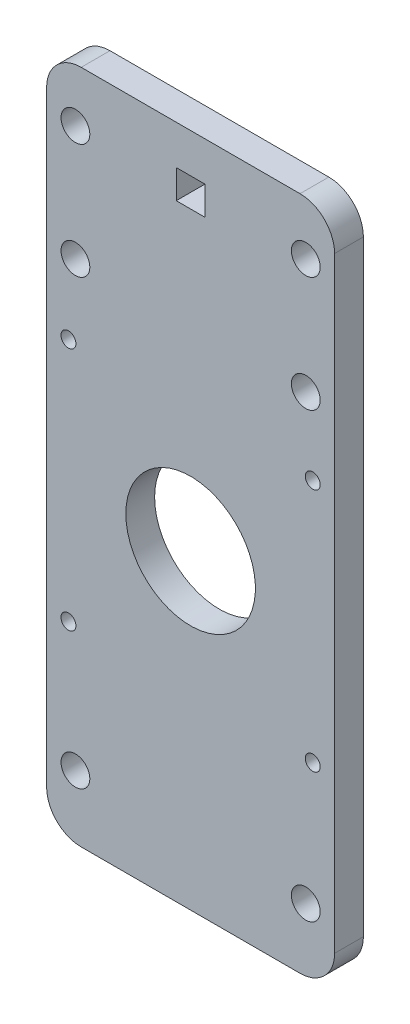
SolidWorks part; units mm, degrees
ref_plane "Front Plane" through (0, 0, 0) normal (0, 0, 1) x (1, 0, 0)
ref_plane "Top Plane" through (0, 0, 0) normal (0, 1, 0) x (1, 0, 0)
ref_plane "Right Plane" through (0, 0, 0) normal (1, 0, 0) x (0, 0, -1)
sketch "Sketch1" plane through (0, 0, 0) normal (0, 0, 1) x (1, 0, 0)
  line L0 (-19.6989, 23.2988) -> (-14.85, 29.7515)
  line L1 (-13.2512, 30.55) -> (13.2512, 30.55)
  line L2 (-20.1, 22.0973) -> (-20.1, -22.0973)
  line L3 (-13.2512, -30.55) -> (13.2512, -30.55)
  line L4 (20.1, 22.0973) -> (20.1, -22.0973)
  line L5 (-20.1, 30.55) -> (20.1, -30.55) construction
  line L6 (-20.1, -30.55) -> (20.1, 30.55) construction
  line L7 (14.85, 29.7515) -> (19.6989, 23.2988)
  line L8 (19.6989, -23.2988) -> (14.85, -29.7515)
  line L9 (-14.85, -29.7515) -> (-19.6989, -23.2988)
  arc A0 (-19.6989, -23.2988) -> (-20.1, -22.0973) centre (-18.1, -22.0973) cw
  arc A1 (-14.85, -29.7515) -> (-13.2512, -30.55) centre (-13.2512, -28.55) ccw
  arc A2 (14.85, -29.7515) -> (13.2512, -30.55) centre (13.2512, -28.55) cw
  arc A3 (19.6989, -23.2988) -> (20.1, -22.0973) centre (18.1, -22.0973) ccw
  arc A4 (19.6989, 23.2988) -> (20.1, 22.0973) centre (18.1, 22.0973) cw
  arc A5 (14.85, 29.7515) -> (13.2512, 30.55) centre (13.2512, 28.55) ccw
  arc A6 (-14.85, 29.7515) -> (-13.2512, 30.55) centre (-13.2512, 28.55) cw
  arc A7 (-19.6989, 23.2988) -> (-20.1, 22.0973) centre (-18.1, 22.0973) ccw
  point P0 (0, 0)
  point P16 (-20.1, -22.765)
  point P19 (-14.25, -30.55)
  point P22 (14.25, -30.55)
  point P25 (20.1, -22.765)
  point P28 (20.1, 22.765)
  point P31 (14.25, 30.55)
  point P34 (-14.25, 30.55)
  point P37 (-20.1, 22.765)
  dimension "D11" = 2
  dimension "D1" = 40.2
  dimension "D2" = 61.1
  dimension "D3" = 5.85
  dimension "D4" = 7.785
  dimension "D5" = 5.85
  dimension "D6" = 7.785
  dimension "D7" = 7.785
  dimension "D8" = 5.85
  dimension "D9" = 5.85
  dimension "D10" = 7.785
extrude "Boss-Extrude1" add sketch "Sketch1" against normal blind 6.35
sketch "Sketch2" plane through (0, 0, -6.35) normal (0, 0, -1) x (-1, 0, 0)
  line L0 (14.85, 29.7515) -> (14.85, -29.7515) construction
  line L1 (-14.85, 29.7515) -> (-14.85, -29.7515) construction
  line L2 (19.6989, 23.2988) -> (-19.6989, 23.2988) construction
  line L3 (20.1, -22.0973) -> (-20.1, -22.0973) construction
  line L4 (0, 30.55) -> (0, -30.55) construction
  line L5 (-13.2512, 30.55) -> (13.2512, 30.55) construction
  line L6 (13.2512, -30.55) -> (-13.2512, -30.55) construction
  circle A0 centre (17.3, 21.9488) radius 1.35
  circle A1 centre (17.3, -0.0512) radius 1.35
  circle A2 centre (17.3, -22.0512) radius 1.35
  circle A3 centre (11, -27.75) radius 1.385
  circle A4 centre (-11, -27.75) radius 1.385
  circle A5 centre (-17.3, -22.0512) radius 1.35
  circle A6 centre (-17.3, -0.0512) radius 1.35
  circle A7 centre (-17.3, 21.9488) radius 1.35
  dimension "D1" = 2.7
  dimension "D5" = 2.77
  dimension "D2" = 22
  dimension "D3" = 22
  dimension "D4" = 17.3
  dimension "D6" = 11
  dimension "D7" = 2.8
extrude "Cut-Extrude1" cut sketch "Sketch2" against normal through all
sketch "Sketch3" plane through (0, 0, -6.35) normal (0, 0, -1) x (-1, 0, 0)
  line L2 (-31.75, 38.2048) -> (31.75, 38.2048)
  line L3 (-31.75, 38.2048) -> (-31.75, -50.6952)
  line L4 (-31.75, -50.6952) -> (31.75, -50.6952)
  line L6 (31.75, 38.2048) -> (31.75, -50.6952)
  line L9 (-19.1605, 23.6188) -> (19.1605, 23.6188)
  line L10 (-19.1605, 23.6188) -> (-19.1605, -23.6188)
  line L11 (-19.1605, -23.6188) -> (19.1605, -23.6188)
  line L12 (19.1605, 23.6188) -> (19.1605, -23.6188)
  circle A0 centre (17.3, 21.9488) radius 1.35 construction
  point P0 (0, 0)
  point P6 (0, 0)
  dimension "D4" = 16.256
  dimension "D1" = 63.5
  dimension "D2" = 88.9
  dimension "D3" = 31.75
extrude "Boss-Extrude2" add sketch "Sketch3" against normal blind 6.35
sketch "Sketch5" plane through (0, 0, 0) normal (0, 0, 1) x (1, 0, 0)
  line L1 (-13.97, 30.9488) -> (13.97, 30.9488)
  line L2 (-13.97, 30.9488) -> (-13.97, -24.9312)
  line L3 (-13.97, -24.9312) -> (13.97, -24.9312)
  line L4 (13.97, 30.9488) -> (13.97, -24.9312)
  circle A0 centre (17.3, 21.9488) radius 1.35 construction
  dimension "D1" = 27.94
  dimension "D2" = 55.88
  dimension "D3" = 9
extrude "Cut-Extrude3" cut sketch "Sketch5" against normal through all
sketch "Sketch6" plane through (0, 0, -6.35) normal (0, 0, -1) x (-1, 0, 0)
  circle A2 centre (-25.4, -36.7252) radius 3.175
  circle A3 centre (25.4, -36.7252) radius 3.175
extrude "Cut-Extrude4" cut sketch "Sketch6" against normal through all
sketch "Sketch7" plane through (0, 0, -6.35) normal (0, 0, -1) x (-1, 0, 0)
  line L1 (-20.8625, 32.0966) -> (20.8625, 32.0966)
  line L2 (-20.8625, 32.0966) -> (-20.8625, -25.7617)
  line L3 (-20.8625, -25.7617) -> (20.8625, -25.7617)
  line L4 (20.8625, 32.0966) -> (20.8625, -25.7617)
  line L5 (-20.8625, 32.0966) -> (20.8625, -25.7617) construction
  line L6 (-20.8625, -25.7617) -> (20.8625, 32.0966) construction
  point P0 (0, 3.1674)
extrude "Boss-Extrude3" add sketch "Sketch7" against normal blind 6.35
sketch "Sketch8" plane through (0, 0, -6.35) normal (0, 0, -1) x (-1, 0, 0)
  line L0 (31.75, 38.2048) -> (-31.75, 38.2048) construction
  circle A0 centre (0, 17.8848) radius 14.2875
  dimension "D1" = 20.32
extrude "Cut-Extrude5" cut sketch "Sketch8" against normal blind 6.35
sketch "Sketch10" plane through (0, 0, -6.35) normal (0, 0, -1) x (-1, 0, 0)
  line L1 (-31.75, 38.2048) -> (31.75, 38.2048)
  line L2 (-31.75, 38.2048) -> (-31.75, 98.2048)
  line L3 (-31.75, 98.2048) -> (31.75, 98.2048)
  line L4 (31.75, 38.2048) -> (31.75, 98.2048)
  line L5 (3.165, 89.5448) -> (-3.165, 89.5448)
  line L6 (3.165, 89.5448) -> (3.165, 83.2148)
  line L7 (3.165, 83.2148) -> (-3.165, 83.2148)
  line L8 (-3.165, 89.5448) -> (-3.165, 83.2148)
  circle A0 centre (-25.4, 86.3798) radius 3.175
  circle A1 centre (-25.4, 60.9798) radius 3.175
  circle A2 centre (25.4, 60.9798) radius 3.175
  circle A3 centre (25.4, 86.3798) radius 3.175
  dimension "D3" = 2
  dimension "D1" = 60
  dimension "D2" = 6.33
  dimension "D4" = 6.33
extrude "Boss-Extrude4" add sketch "Sketch10" against normal blind 6.35
fillet "Fillet1" radius 7.62 4 edges at (-31.75, -50.6952, -3.175) (31.75, -50.6952, -3.175) (-31.75, 98.2048, -3.175) (31.75, 98.2048, -3.175)
sketch "Sketch11" plane through (0, 0, 0) normal (0, 0, 1) x (1, 0, 0)
  circle A0 centre (-26.94, 44.8248) radius 1.65
  circle A4 centre (26.94, 44.8248) radius 1.65
  circle A5 centre (-26.94, -9.056) radius 1.65
  circle A6 centre (26.94, -9.056) radius 1.65
extrude "Cut-Extrude6" cut sketch "Sketch11" against normal through all
